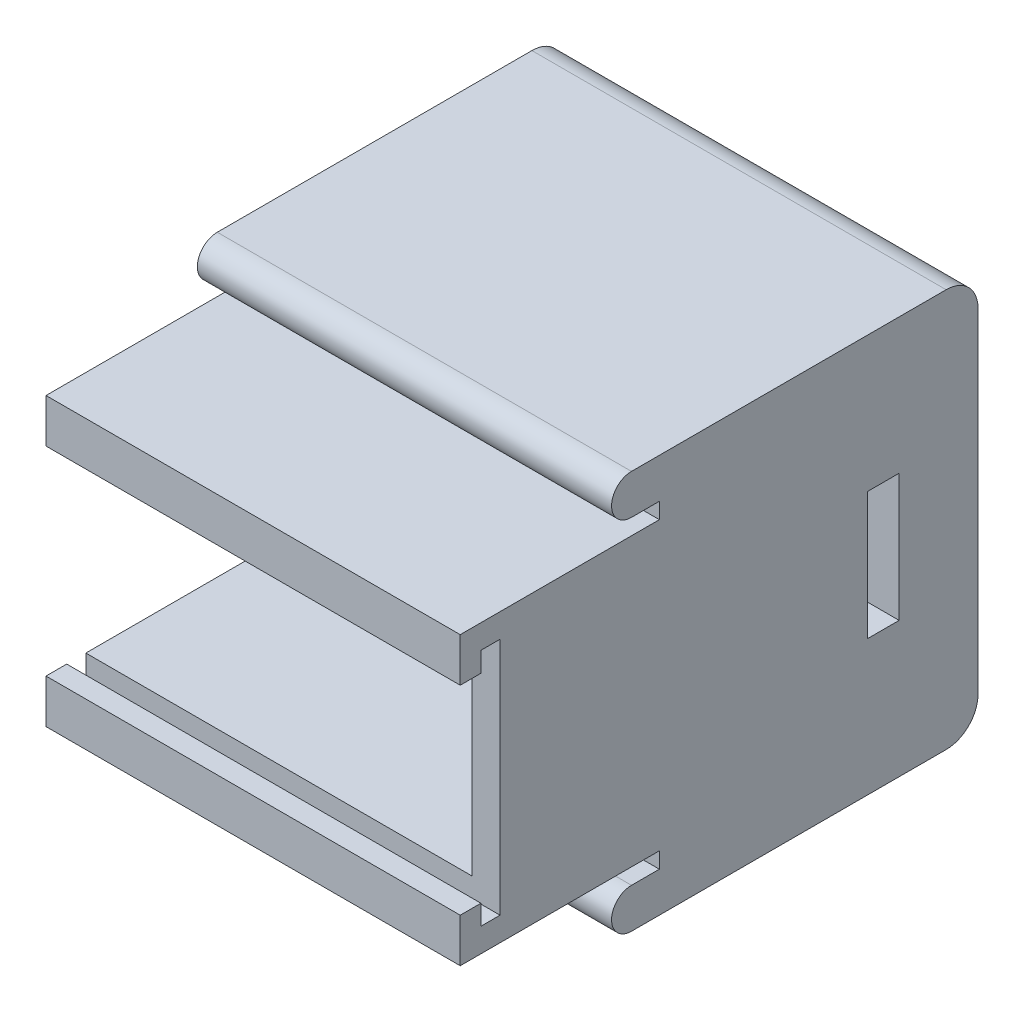
SolidWorks part; units mm, degrees
ref_plane "Спереди" through (0, 0, 0) normal (0, 0, 1) x (1, 0, 0)
ref_plane "Сверху" through (0, 0, 0) normal (0, 1, 0) x (1, 0, 0)
ref_plane "Справа" through (0, 0, 0) normal (1, 0, 0) x (0, 0, -1)
sketch "Эскиз1" plane through (0, 0, 0) normal (0, 0, 1) x (1, 0, 0)
  line L0 (13, 12.5) -> (-13, -12.5) construction
  line L1 (-13, 12.5) -> (13, 12.5)
  line L2 (-13, 12.5) -> (-13, -12.5)
  line L3 (-13, -12.5) -> (13, -12.5)
  line L4 (13, 12.5) -> (13, -12.5)
  dimension "D1" = 25
  dimension "D2" = 26
extrude "Бобышка-Вытянуть1" add sketch "Эскиз1" along normal blind 20
sketch "Эскиз3" plane through (13, 0, 0) normal (1, 0, 0) x (0, 0, -1)
  line L0 (-20, 12.5) -> (-21.75, 12.5)
  line L1 (-20, 10) -> (-21.75, 10)
  line L2 (-20, -12.5) -> (-20, 12.5) construction
  line L3 (-20, 12.5) -> (-20, 10) construction
  line L8 (0, -12.5) -> (0, 12.5)
  line L9 (0, 12.5) -> (-20, 12.5)
  line L10 (-20, 12.5) -> (-20, -12.5)
  line L11 (-20, -12.5) -> (0, -12.5)
  line L14 (-20, 12.5) -> (-20, 10)
  arc A0 (-21.75, 12.5) -> (-21.75, 10) centre (-21.75, 11.25) ccw
  dimension "D1" = 2.5
  dimension "D2" = 1.75
  dimension "D3" = 0
extrude "Бобышка-Вытянуть3" add sketch "Эскиз3" against normal through all
mirror "Зеркальное отражение1" about plane through (0, 0, 0) normal (0, 1, 0) of "Бобышка-Вытянуть3"
sketch "Эскиз4" plane through (0, 0, 20) normal (0, 0, 1) x (1, 0, 0)
  line L0 (-13, 10) -> (-13, -10) construction
  line L1 (-13, 9) -> (13, 9)
  line L2 (-13, 9) -> (-13, -9)
  line L3 (-13, -9) -> (13, -9)
  line L4 (13, 9) -> (13, -9)
  line L5 (13, -10) -> (13, 10) construction
  line L6 (13, 9) -> (-13, -9) construction
  line L7 (-13, 10) -> (13, 10) construction
  dimension "D1" = 1
extrude "Бобышка-Вытянуть4" add sketch "Эскиз4" along normal blind 10
sketch "Эскиз5" plane through (0, 0, 30) normal (0, 0, 1) x (1, 0, 0)
  line L0 (11.25, 6.25) -> (-11.25, -6.25) construction
  line L1 (-11.25, 6.25) -> (11.25, 6.25)
  line L2 (-11.25, 6.25) -> (-11.25, -6.25)
  line L3 (-11.25, -6.25) -> (11.25, -6.25)
  line L4 (11.25, 6.25) -> (11.25, -6.25)
  dimension "D1" = 22.5
  dimension "D2" = 12.5
extrude "Вырез-Вытянуть1" cut sketch "Эскиз5" against normal blind 23.05
sketch "Эскиз8" plane through (-13, 0, 0) normal (-1, 0, 0) x (0, 0, 1)
  line L0 (30, 6.25) -> (30, -6.25) construction
  line L1 (30, 9) -> (30, -9) construction
  line L2 (30, -6.25) -> (13.2, -6.25)
  line L3 (30, 6.25) -> (13.2, 6.25)
  line L4 (30, 6.25) -> (30, -6.25)
  line L5 (0, 0) -> (30, 0) construction
  arc A0 (13.2, 6.25) -> (13.2, -6.25) centre (13.2, 0) ccw
  dimension "D1" = 12.5
  dimension "D2" = 16.8
extrude "Вырез-Вытянуть5" cut sketch "Эскиз8" against normal blind 3.55
sketch "Эскиз9" plane through (0, 0, 6.95) normal (0, 0, 1) x (1, 0, 0)
  line L1 (11.256, 4) -> (4.256, 4)
  line L2 (11.256, 4) -> (11.256, -4)
  line L3 (11.256, -4) -> (4.256, -4)
  line L4 (4.256, 4) -> (4.256, -4)
  line L5 (0, 0) -> (4.256, 0) construction
  dimension "D1" = 7
  dimension "D2" = 8
extrude "Вырез-Вытянуть6" cut sketch "Эскиз9" against normal blind 2
sketch "Эскиз10" plane through (11.256, 0, 0) normal (-1, 0, 0) x (0, 0, 1)
  line L0 (4.95, -4) -> (4.95, 4) construction
  line L1 (4.95, 4) -> (6.95, 4)
  line L2 (4.95, 4) -> (4.95, -4)
  line L3 (4.95, -4) -> (6.95, -4)
  line L4 (6.95, 4) -> (6.95, -4)
  line L5 (6.95, -4) -> (6.95, 4) construction
  line L6 (4.95, -4) -> (6.95, -4) construction
extrude "Вырез-Вытянуть7" cut sketch "Эскиз10" against normal blind 2
sketch "Эскиз12" plane through (13, 0, 0) normal (1, 0, 0) x (0, 0, -1)
  line L0 (-30, 9) -> (-32.5, 9)
  line L1 (-32.5, 9) -> (-32.5, 6.25)
  line L2 (-32.5, 6.25) -> (-31.2, 6.25)
  line L3 (-31.2, 6.25) -> (-31.2, 7.5)
  line L4 (-31.2, 7.5) -> (-30, 7.5)
  line L5 (-30, -9) -> (-30, 9) construction
  line L6 (-30, 7.5) -> (-30, 9)
  line L7 (-30, 6.25) -> (-13.2, 6.25) construction
  dimension "D1" = 1.5
  dimension "D2" = 2.5
  dimension "D3" = 1.3
extrude "Бобышка-Вытянуть5" add sketch "Эскиз12" against normal through all
mirror "Зеркальное отражение2" about plane through (0, 0, 0) normal (0, 1, 0) of "Бобышка-Вытянуть5"
fillet "Скругление1" radius 2 2 edges at (0, -12.5, 0) (0, 12.5, 0)
